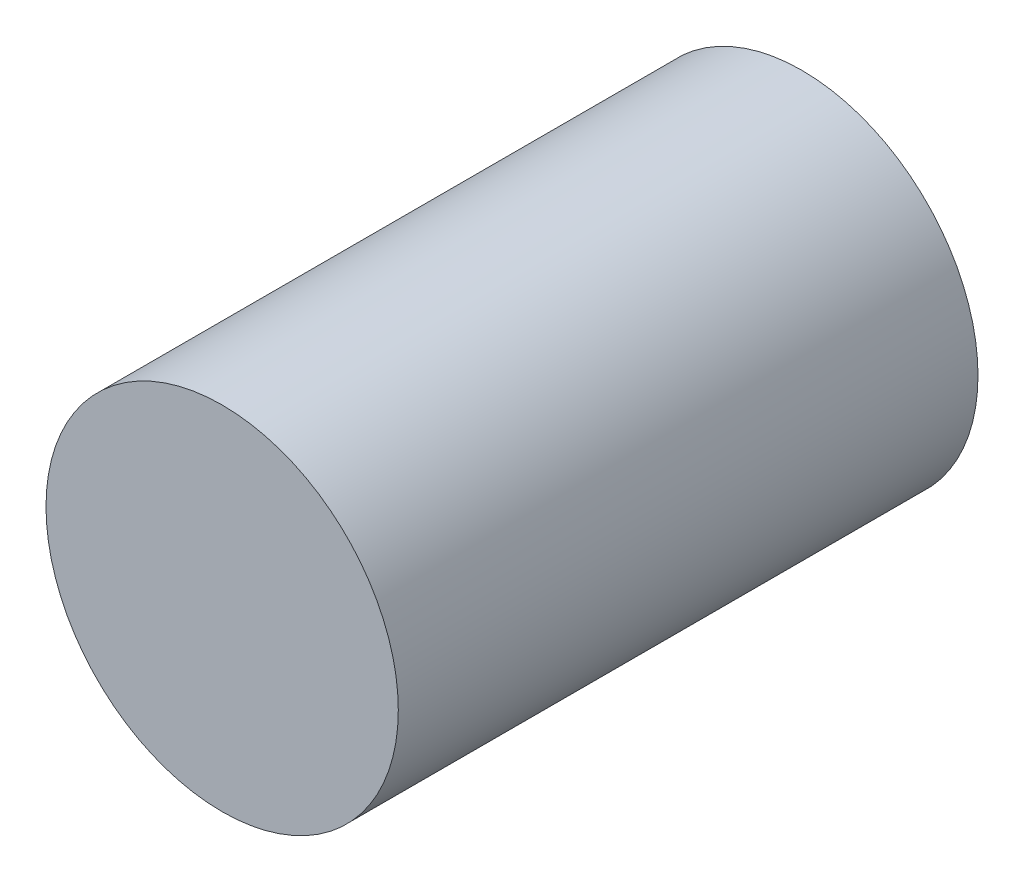
SolidWorks part; units mm, degrees
ref_plane "Front Plane" through (0, 0, 0) normal (0, 0, 1) x (1, 0, 0)
ref_plane "Top Plane" through (0, 0, 0) normal (0, 1, 0) x (1, 0, 0)
ref_plane "Right Plane" through (0, 0, 0) normal (1, 0, 0) x (0, 0, -1)
sketch "Sketch1" plane through (0, 0, 0) normal (0, 0, 1) x (1, 0, 0)
  circle A0 centre (0, 0) radius 11
  dimension "D1" = 22
extrude "Boss-Extrude1" add sketch "Sketch1" along normal blind 36.2
